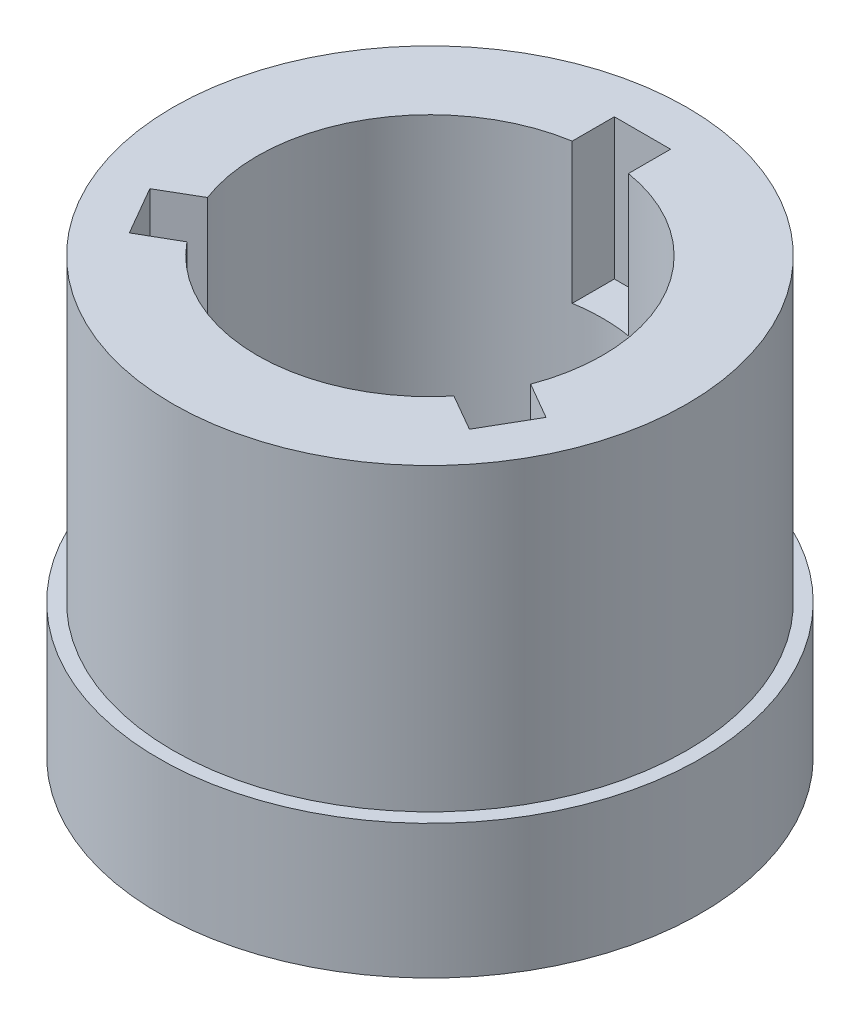
SolidWorks part; units mm, degrees
ref_plane "Front Plane" through (0, 0, 0) normal (0, 0, 1) x (1, 0, 0)
ref_plane "Top Plane" through (0, 0, 0) normal (0, 1, 0) x (1, 0, 0)
ref_plane "Right Plane" through (0, 0, 0) normal (1, 0, 0) x (0, 0, -1)
sketch "Sketch1" plane through (0, 0, 0) normal (0, 0, 1) x (1, 0, 0)
  line L0 (0, 0) -> (-35, 0) construction
  line L2 (0, 0) -> (0, 59.2741) construction
  line L16 (-23.2243, -43.1702) -> (-30.7243, -43.1702)
  line L17 (-30.7243, -43.1702) -> (-48.2243, -35.3812)
  line L18 (-48.2243, -35.3812) -> (-48.2243, -11.5424)
  line L19 (-48.2243, -11.5424) -> (-45.7243, -11.5424)
  line L20 (-45.7243, -11.5424) -> (-45.7243, 41.8298)
  line L21 (-45.7243, 41.8298) -> (-38.2243, 41.8298)
  line L22 (-38.2243, 41.8298) -> (-38.2243, 16.8298)
  line L23 (-38.2243, 16.8298) -> (-30.7243, 16.8298)
  line L24 (-30.7243, 16.8298) -> (-30.7243, -29.4383)
  arc A1 (-30.7243, -29.4383) -> (-23.2243, -43.1702) centre (-14.4033, -29.4383) ccw
  dimension "D1" = 35
  dimension "D3" = 7.5
  dimension "D4" = 7.5
  dimension "D5" = 25
  dimension "D6" = 7.5
  dimension "D7" = 85
revolve "Revolve1" add sketch "Sketch1" angle 360 about L2
sketch "Sketch3" plane through (0, 16.8298, 0) normal (0, 1, 0) x (1, 0, 0)
  circle A0 centre (0, 0) radius 30.7243 construction
  circle A1 centre (0, 0) radius 38.2243
  circle A2 centre (0, 0) radius 38.2243
  circle A3 centre (0, 0) radius 30.7243
  dimension "D1" = 0
extrude "Boss-Extrude1" add sketch "Sketch3" along normal blind 25
sketch "Sketch4" plane through (0, 41.8298, 0) normal (0, 1, 0) x (1, 0, 0)
  line L0 (-5, 37.8147) -> (-5, 30.3147)
  line L1 (5, 37.8147) -> (5, 30.3147)
  line L2 (30.255, -23.2291) -> (23.7533, -19.4875)
  line L3 (35.2445, -14.587) -> (28.7533, -10.8272)
  line L4 (-35.2445, -14.587) -> (-28.7533, -10.8272)
  line L5 (-30.255, -23.2291) -> (-23.7533, -19.4875)
  line L6 (-5, 37.8147) -> (5, 37.8147)
  line L7 (30.255, -23.2291) -> (35.2445, -14.587)
  line L8 (-30.255, -23.2291) -> (-35.2445, -14.587)
  arc A4 (-28.7533, -10.8272) -> (-23.7533, -19.4875) centre (0, 0) ccw
  arc A5 (5, 30.3147) -> (-5, 30.3147) centre (0, 0) ccw
  arc A7 (23.7533, -19.4875) -> (28.7533, -10.8272) centre (0, 0) ccw
  point P13 (-13.7988, -12.2809)
  dimension "D1" = 7.5
extrude "Cut-Extrude1" cut sketch "Sketch4" against normal blind 25
